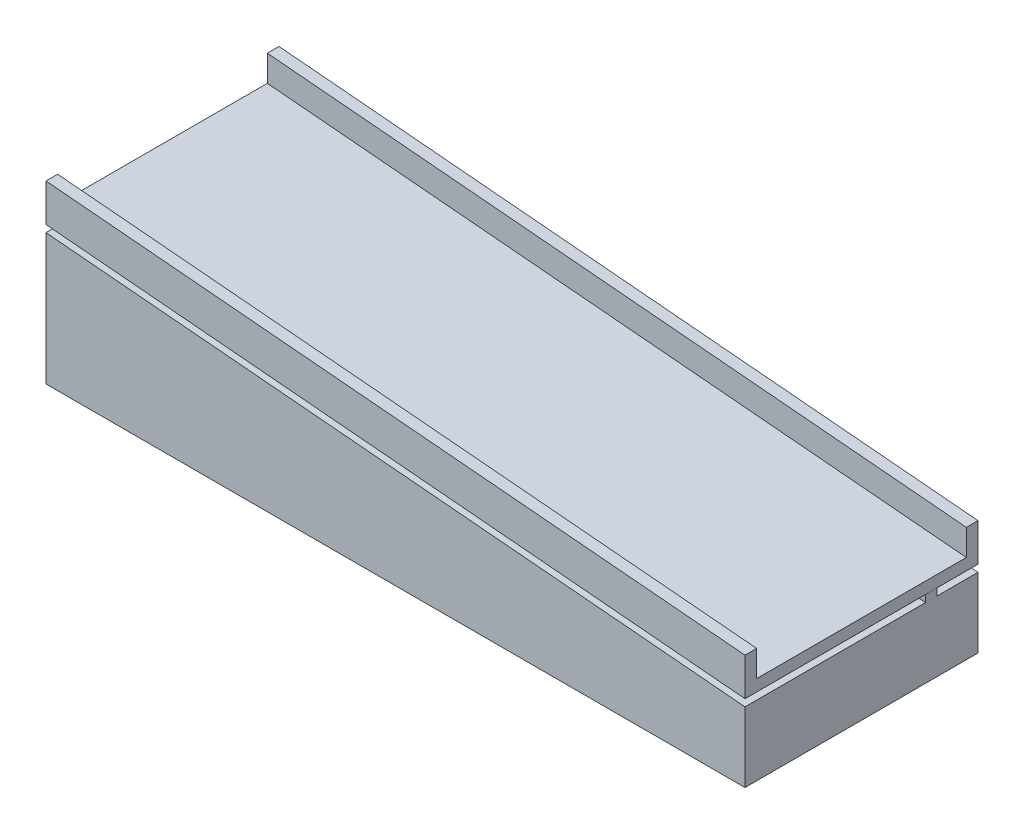
SolidWorks part; units mm, degrees
ref_plane "Alzado" through (0, 0, 0) normal (0, 0, 1) x (1, 0, 0)
ref_plane "Planta" through (0, 0, 0) normal (0, 1, 0) x (1, 0, 0)
ref_plane "Vista lateral" through (0, 0, 0) normal (1, 0, 0) x (0, 0, -1)
sketch "Croquis1" plane through (0, 0, 0) normal (0, 0, 1) x (1, 0, 0)
  line L0 (0, 0) -> (0, 56.2466)
  line L1 (0, 56.2466) -> (300, 30)
  line L2 (300, 30) -> (300, 0)
  line L3 (300, 0) -> (0, 0)
  line L4 (300, 30) -> (204.1547, 30) construction
  dimension "D1" = 300
  dimension "D2" = 5
  dimension "D3" = 30
extrude "Saliente-Extruir1" add sketch "Croquis1" along normal blind 100
ref_plane "Plano1" through (0, 0, 20) normal (0, 0, 1) x (1, 0, 0)
sketch "Croquis3" plane through (0, 0, 20) normal (0, 0, 1) x (1, 0, 0)
  line L0 (0, 56.2466) -> (300, 30)
  line L1 (300, 30) -> (300, 33)
  line L2 (300, 33) -> (0, 59.2466)
  line L3 (0, 59.2466) -> (0, 56.2466)
  dimension "D1" = 3
extrude "Saliente-Extruir2" add sketch "Croquis3" along normal mid plane 5
sketch "Croquis4" plane through (0, 0, 20) normal (0, 0, 1) x (1, 0, 0)
  line L0 (0, 59.2466) -> (300, 33)
sketch "Croquis5" plane through (0, 0, 0) normal (-1, 0, 0) x (0, 0, 1)
  line L0 (95, 75.4577) -> (100, 75.4577)
  line L1 (0, 59.2578) -> (100, 59.2578)
  line L2 (0, 59.2578) -> (0, 75.4577)
  line L3 (0, 75.4577) -> (5, 75.4577)
  line L4 (100, 59.2578) -> (100, 75.4577)
  line L6 (5, 75.4577) -> (5, 64.2578)
  line L7 (5, 64.2578) -> (95, 64.2578)
  line L8 (95, 75.4577) -> (95, 64.2578)
  dimension "D1" = 5
  dimension "D2" = 5
  dimension "D3" = 5
  dimension "D4" = 100
sweep "Barrer1" add profiles "Croquis5" path "Croquis4"
